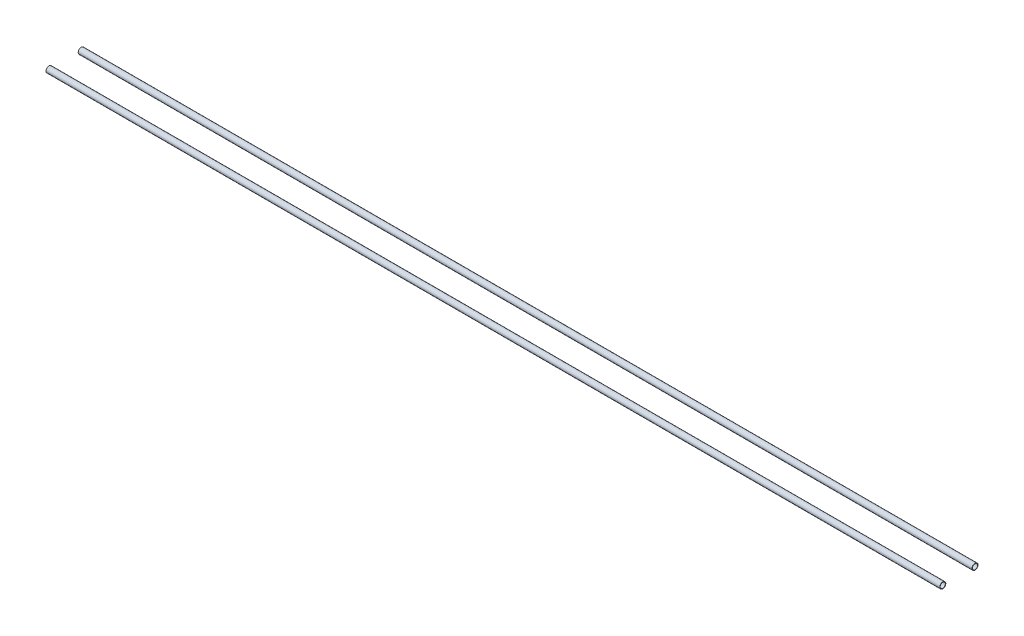
SolidWorks part; units mm, degrees
material "carbon fiber spar"
ref_plane "Front Plane" through (0, 0, 0) normal (0, 0, 1) x (1, 0, 0)
ref_plane "Top Plane" through (0, 0, 0) normal (0, 1, 0) x (1, 0, 0)
ref_plane "Right Plane" through (0, 0, 0) normal (1, 0, 0) x (0, 0, -1)
sketch "Sketch2" plane through (0, 0, 0) normal (1, 0, 0) x (0, 0, -1)
  circle A0 centre (0, 0) radius 7
  circle A1 centre (75, 0) radius 7
  circle A2 centre (0, 0) radius 6
  circle A3 centre (75, 0) radius 6
  dimension "D1" = 14
  dimension "D2" = 14
  dimension "D3" = 75
  dimension "D4" = 1
  dimension "D5" = 1
extrude "Boss-Extrude1" add sketch "Sketch2" along normal mid plane 2080
